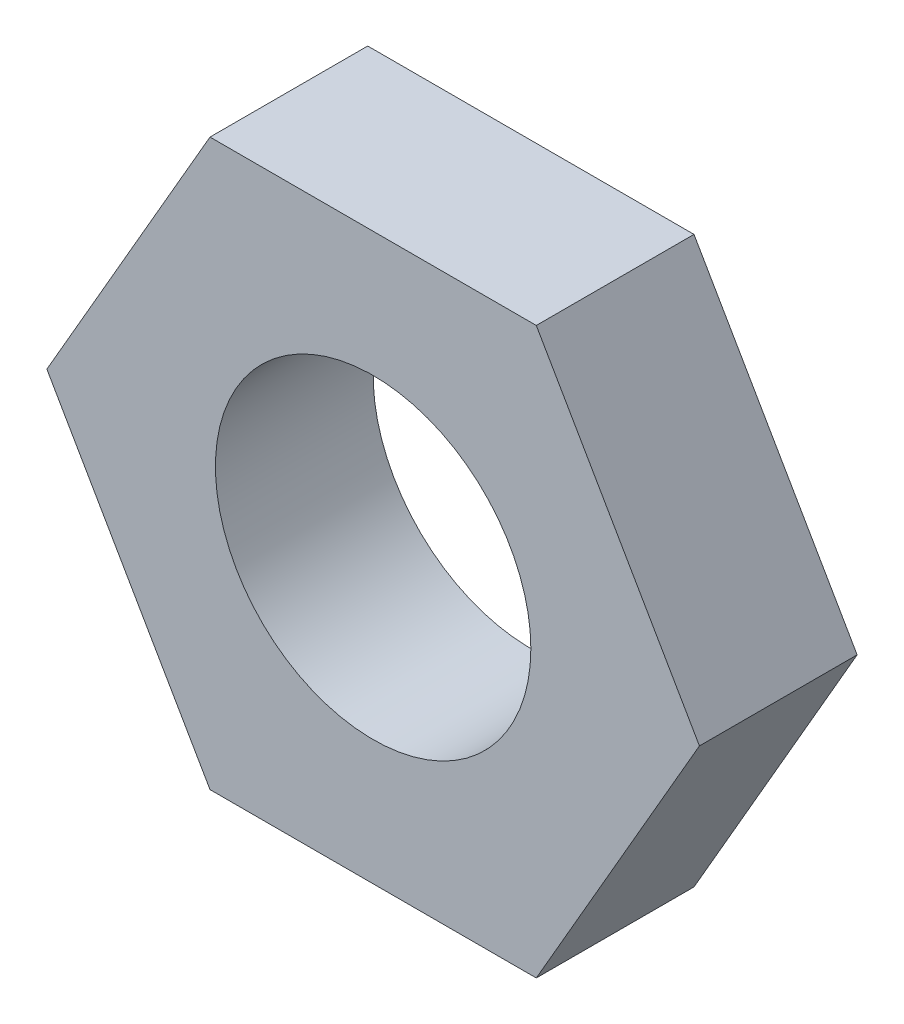
SolidWorks part; units mm, degrees
ref_plane "Plan de face" through (0, 0, 0) normal (0, 0, 1) x (1, 0, 0)
ref_plane "Plan de dessus" through (0, 0, 0) normal (0, 1, 0) x (1, 0, 0)
ref_plane "Plan de droite" through (0, 0, 0) normal (1, 0, 0) x (0, 0, -1)
sketch "Esquisse1" plane through (0, 0, 0) normal (0, 0, 1) x (1, 0, 0)
  line L1 (6.2065, 0) -> (3.1033, 5.375)
  line L2 (3.1033, 5.375) -> (-3.1033, 5.375)
  line L3 (-3.1033, 5.375) -> (-6.2065, 0)
  line L4 (-6.2065, 0) -> (-3.1033, -5.375)
  line L5 (-3.1033, -5.375) -> (3.1033, -5.375)
  line L6 (3.1033, -5.375) -> (6.2065, 0)
  circle A0 centre (0, 0) radius 5.375 construction
  circle A1 centre (0, 0) radius 3
  dimension "D2" = 6
  dimension "D1" = 10.75
extrude "Boss.-Extru.1" add sketch "Esquisse1" along normal blind 3
